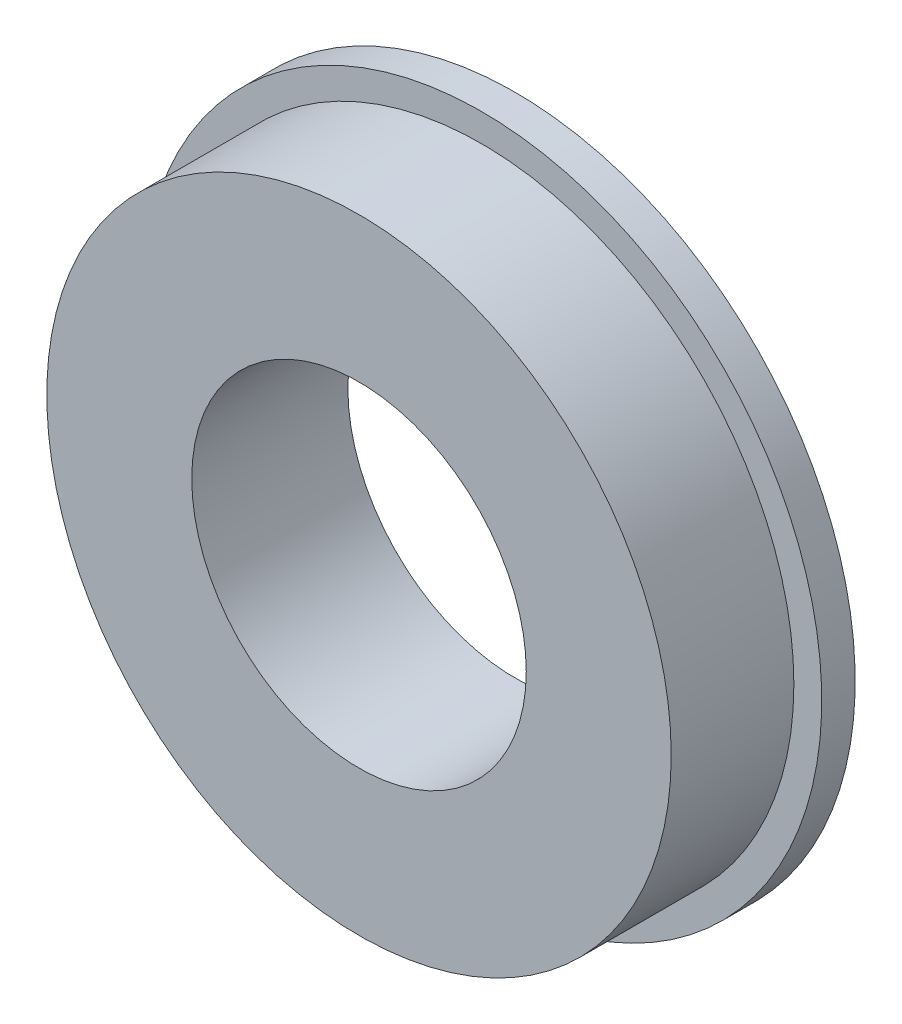
SolidWorks part; units mm, degrees
ref_plane "前视基准面" through (0, 0, 0) normal (0, 0, 1) x (1, 0, 0)
ref_plane "上视基准面" through (0, 0, 0) normal (0, 1, 0) x (1, 0, 0)
ref_plane "右视基准面" through (0, 0, 0) normal (1, 0, 0) x (0, 0, -1)
sketch "草图1" plane through (0, 0, 0) normal (0, 0, 1) x (1, 0, 0)
  circle A0 centre (0, 0) radius 7.5
  circle A1 centre (0, 0) radius 14
extrude "凸台-拉伸1" add sketch "草图1" along normal blind 5.5
sketch "草图2" plane through (0, 0, 0) normal (0, 0, -1) x (-1, 0, 0)
  circle A0 centre (0, 0) radius 7.5
  circle A1 centre (0, 0) radius 15.25
extrude "凸台-拉伸3" add sketch "草图2" along normal blind 1.5
